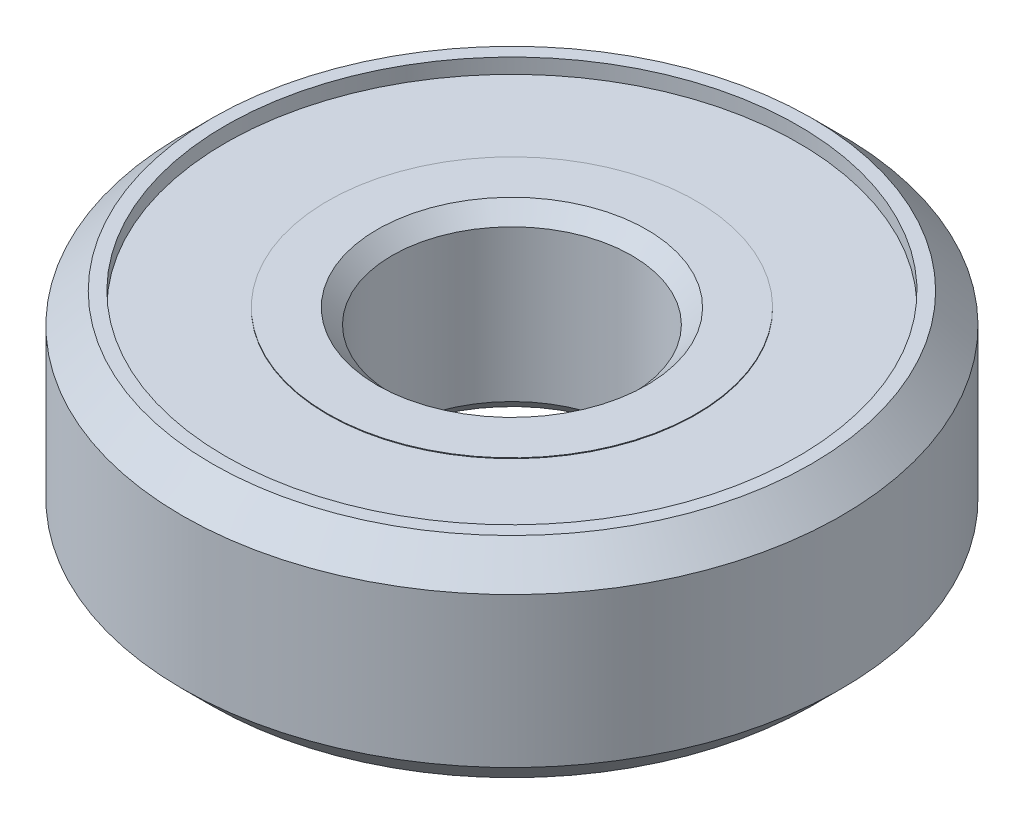
SolidWorks part; units mm, degrees
ref_plane "Front Plane" through (0, 0, 0) normal (0, 0, 1) x (1, 0, 0)
ref_plane "Top Plane" through (0, 0, 0) normal (0, 1, 0) x (1, 0, 0)
ref_plane "Right Plane" through (0, 0, 0) normal (1, 0, 0) x (0, 0, -1)
sketch "Sketch1" plane through (0, 0, 0) normal (0, 1, 0) x (1, 0, 0)
  circle A0 centre (0, 0) radius 11
  circle A1 centre (0, 0) radius 4
  dimension "D1" = 8
  dimension "D2" = 22
extrude "Boss-Extrude1" add sketch "Sketch1" along normal blind 7
chamfer "Chamfer1" distance 1 angle 45 2 edges at (0, 7, 11) (0, 0, 11)
sketch "Sketch2" plane through (0, 7, 0) normal (0, 1, 0) x (1, 0, 0)
  circle A0 centre (0, 0) radius 9.5605
extrude "Cut-Extrude1" cut sketch "Sketch2" against normal blind 0.5
sketch "Sketch3" plane through (0, 6.5, 0) normal (0, 1, 0) x (1, 0, 0)
  circle A0 centre (0, 0) radius 6.1525
  circle A1 centre (0, 0) radius 4
extrude "Boss-Extrude2" add sketch "Sketch3" along normal blind 0.025
chamfer "Chamfer2" distance 0.5 angle 45 1 edges at (0, 6.525, 4)
ref_plane "Plane1" through (0, 3.5, 0) normal (0, -1, 0) x (-1, 0, 0)
mirror "Mirror3" about plane through (0, 3.5, 0) normal (0, -1, 0) of "Boss-Extrude2", "Chamfer2", "Cut-Extrude1"
